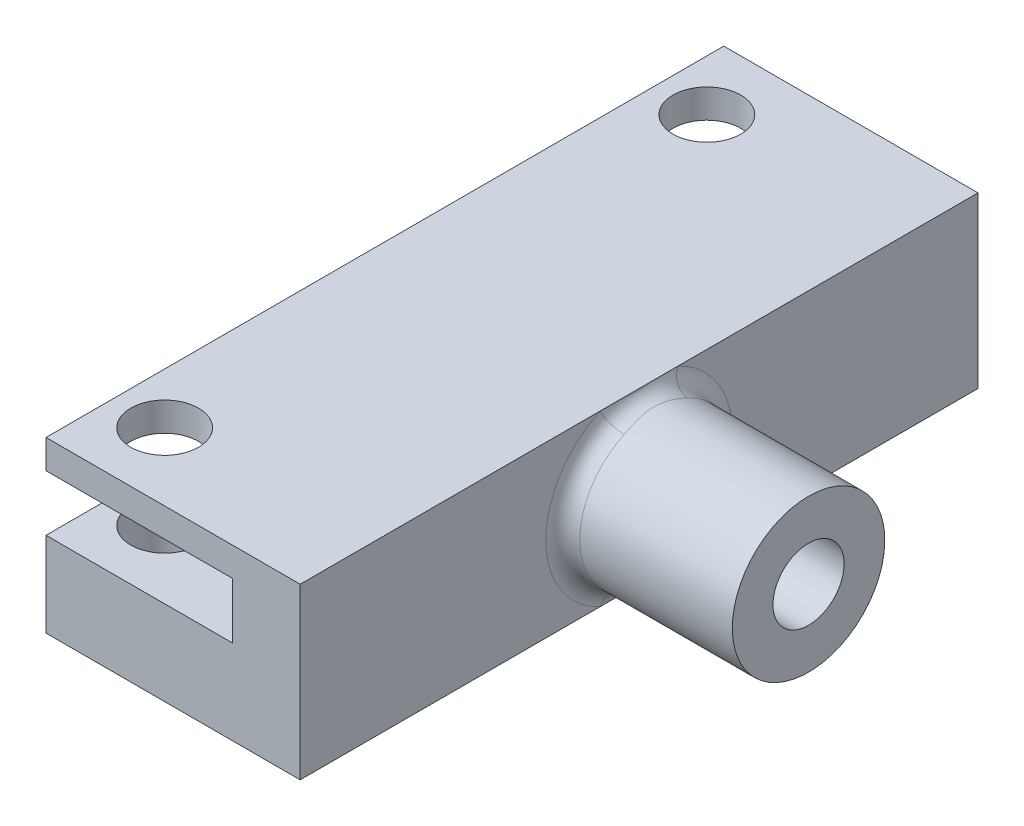
SolidWorks part; units mm, degrees
ref_plane "Front Plane" through (0, 0, 0) normal (0, 0, 1) x (1, 0, 0)
ref_plane "Top Plane" through (0, 0, 0) normal (0, 1, 0) x (1, 0, 0)
ref_plane "Right Plane" through (0, 0, 0) normal (1, 0, 0) x (0, 0, -1)
sketch "Sketch1" plane through (0, 0, 0) normal (0, 0, 1) x (1, 0, 0)
  line L0 (-11, 3.3) -> (-11, 5)
  line L1 (-11, 5) -> (4, 5)
  line L2 (4, 5) -> (4, -5)
  line L3 (4, -5) -> (-11, -5)
  line L4 (-11, -5) -> (-11, 0)
  line L5 (-11, 0) -> (0, 0)
  line L6 (0, 0) -> (0, 3.3)
  line L7 (0, 3.3) -> (-11, 3.3)
  dimension "D1" = 10
  dimension "D2" = 10
  dimension "D3" = 3.3
  dimension "D4" = 5
  dimension "D5" = 1.7
  dimension "D6" = 15
  dimension "D7" = 11
extrude "Boss-Extrude1" add sketch "Sketch1" along normal blind 40
sketch "Sketch4" plane through (4, 0, 0) normal (1, 0, 0) x (0, 0, -1)
  line L1 (-40, -5) -> (-40, 5) construction
  line L2 (-40, 5) -> (0, 5) construction
  circle A0 centre (-20, 0) radius 4.5
  circle A1 centre (-20, 0) radius 2.1
  point P0 (0, 0)
  point P10 (-40, 0)
  point P12 (-20, 5)
  dimension "D1" = 4.2
  dimension "D2" = 9
extrude "Boss-Extrude4" add sketch "Sketch4" along normal blind 10
fillet "Fillet2" radius 1 1 edges at (4, 4.5, 20)
sketch "Sketch5" plane through (0, 5, 0) normal (0, 1, 0) x (1, 0, 0)
  line L0 (-11, -40) -> (-11, 0) construction
  line L1 (4, -40) -> (-11, -40) construction
  line L2 (4, 0) -> (-11, 0) construction
  circle A0 centre (-8, -36) radius 2
  circle A1 centre (-8, -4) radius 2
  dimension "D2" = 4
  dimension "D4" = 4
  dimension "D1" = 3
  dimension "D3" = 4
extrude "Cut-Extrude1" cut sketch "Sketch5" against normal through all
